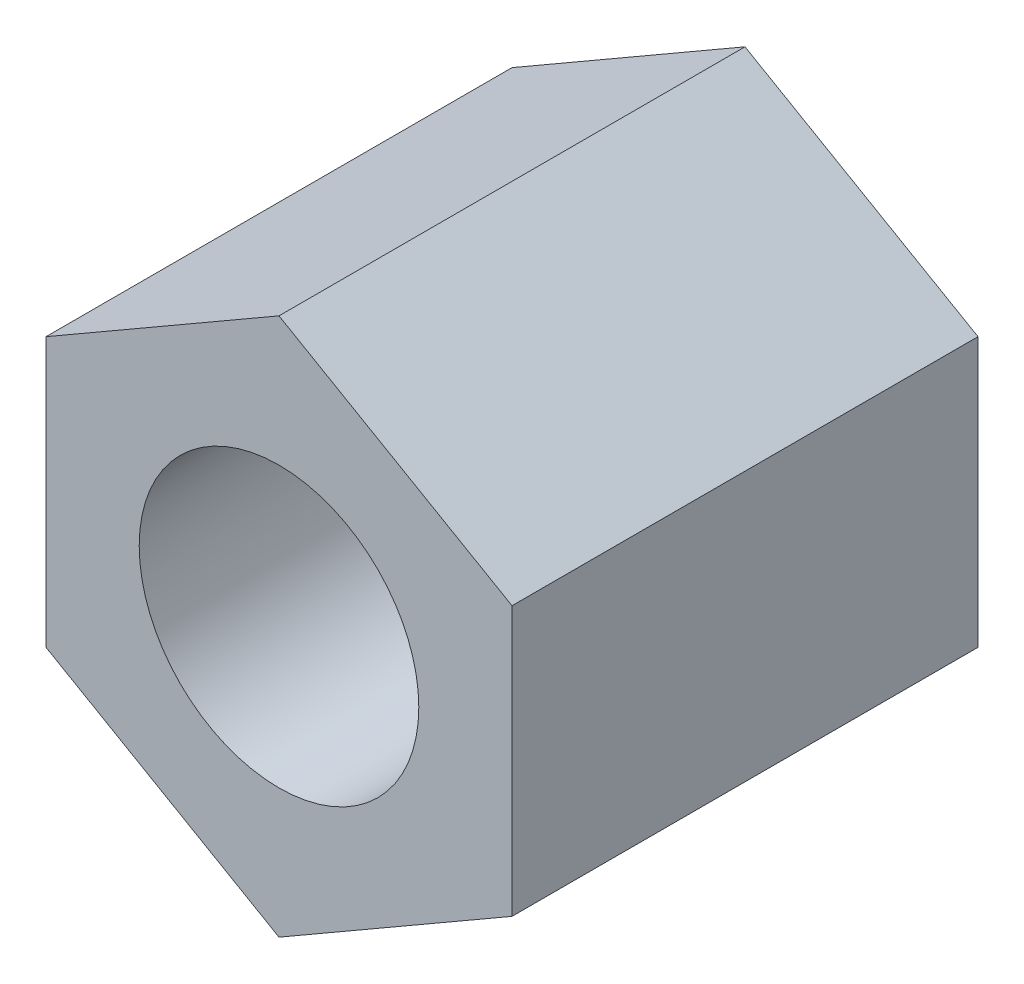
SolidWorks part; units mm, degrees
ref_plane "正面" through (0, 0, 0) normal (0, 0, 1) x (1, 0, 0)
ref_plane "平面" through (0, 0, 0) normal (0, 1, 0) x (1, 0, 0)
ref_plane "右側面" through (0, 0, 0) normal (1, 0, 0) x (0, 0, -1)
sketch "ｽｹｯﾁ1" plane through (0, 0, 0) normal (0, 0, 1) x (1, 0, 0)
  line L1 (0, -2.8868) -> (2.5, -1.4434)
  line L2 (2.5, -1.4434) -> (2.5, 1.4434)
  line L3 (2.5, 1.4434) -> (0, 2.8868)
  line L4 (0, 2.8868) -> (-2.5, 1.4434)
  line L5 (-2.5, 1.4434) -> (-2.5, -1.4434)
  line L6 (-2.5, -1.4434) -> (0, -2.8868)
  circle A0 centre (0, 0) radius 2.5 construction
  circle A1 centre (0, 0) radius 1.5
  dimension "D1" = 5
  dimension "D2" = 3
extrude "ﾎﾞｽ - 押し出し1" add sketch "ｽｹｯﾁ1" along normal blind 5
sketch "ｽｹｯﾁ3" plane through (0, 0, 0) normal (0, 0, 1) x (1, 0, 0)
  circle A0 centre (0, 0) radius 1.5
curve "ﾍﾘｶﾙ ｶｰﾌﾞ/ｽﾊﾟｲﾗﾙ ｶｰﾌﾞ1" pitch 0.5 height 40 turns 80
sketch "ｽｹｯﾁ5" plane through (0, 0, 0) normal (0, 1, 0) x (1, 0, 0)
  line L0 (1.5, 0) -> (1.5, 0.44)
  line L1 (1.5, 0.44) -> (1.77, 0.2841)
  line L2 (1.77, 0.2841) -> (1.77, 0.1559)
  line L3 (1.77, 0.1559) -> (1.5, 0)
  dimension "D1" = 0.44
  dimension "D2" = 60
  dimension "D3" = 60
  dimension "D4" = 0.27
sketch "ｽｹｯﾁ7" plane through (0, 0, 0) normal (0, 0, -1) x (-1, 0, 0)
  circle A0 centre (0, 0) radius 1.5
curve "ﾍﾘｶﾙ ｶｰﾌﾞ/ｽﾊﾟｲﾗﾙ ｶｰﾌﾞ2" pitch 0.5 height 20 turns 40
